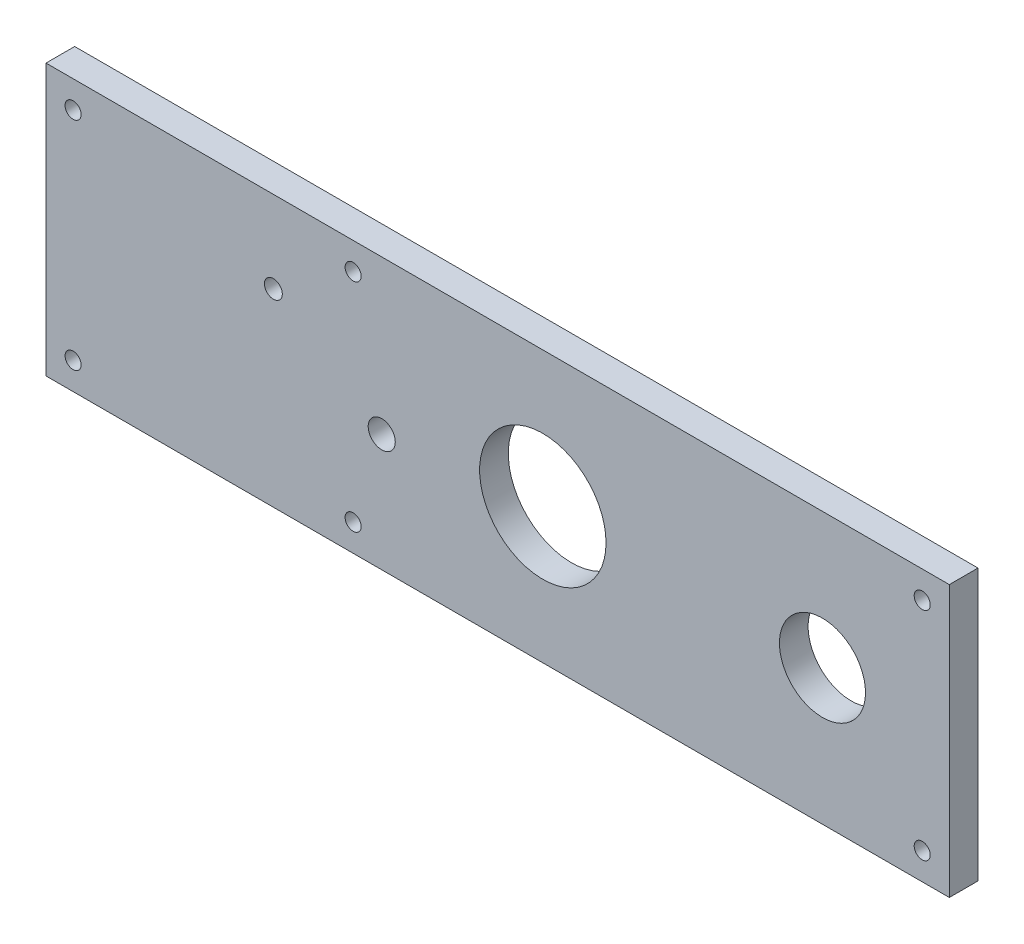
SolidWorks part; units mm, degrees
ref_plane "Front Plane" through (0, 0, 0) normal (0, 0, 1) x (1, 0, 0)
ref_plane "Top Plane" through (0, 0, 0) normal (0, 1, 0) x (1, 0, 0)
ref_plane "Right Plane" through (0, 0, 0) normal (1, 0, 0) x (0, 0, -1)
sketch "Sketch1" plane through (0, 0, 0) normal (0, 0, 1) x (1, 0, 0)
  line L0 (100, 15) -> (0, 15) construction
  line L1 (0, 0) -> (100, 0)
  line L2 (0, 0) -> (0, 30)
  line L3 (0, 30) -> (100, 30)
  line L4 (100, 0) -> (100, 30)
  circle A0 centre (55, 15) radius 6.9977
  circle A1 centre (37.1667, 13) radius 1.4986
  circle A2 centre (25.1698, 20.9334) radius 0.9906
  circle A3 centre (37.1667, 13) radius 11.4777 construction
  circle A4 centre (25.1698, 20.9334) radius 7.1501 construction
  circle A5 centre (55, 15) radius 12.827 construction
  circle A6 centre (16, 15) radius 14 construction
  circle A7 centre (37.1667, 13) radius 5.1181 construction
  point P7 (55, 15)
  point P8 (37.1667, 13)
  point P9 (25.1698, 20.9334)
  point P19 (16, 15)
  dimension "D6" = 13.9954
  dimension "D7" = 2.9972
  dimension "D8" = 1.9812
  dimension "D9" = 25.654
  dimension "D10" = 22.9553
  dimension "D11" = 14.3002
  dimension "D13" = 28
  dimension "D14" = 10.2362
  dimension "D1" = 17.9451
  dimension "D2" = 14.3828
  dimension "D3" = 30
  dimension "D4" = 100
  dimension "D5" = 55
  dimension "D12" = 10.922
  dimension "D15" = 16
  dimension "D16" = 13
extrude "Boss-Extrude2" add sketch "Sketch1" along normal blind 3.175
hole_wizard "#2-56 Tapped Hole1" positions "Sketch3" profile "Sketch2" tap size "#2-56" standard "ANSI Inch" end condition through all
sketch "Sketch3" plane through (0, 0, 3.175) normal (0, 0, 1) x (1, 0, 0)
  line L0 (97, 30) -> (97, 0) construction
  line L1 (100, 30) -> (0, 30) construction
  line L2 (0, 0) -> (100, 0) construction
  line L4 (100, 0) -> (100, 30) construction
  line L6 (3, 30) -> (3, 0) construction
  line L8 (0, 30) -> (0, 0) construction
  line L10 (34, 30) -> (34, 0) construction
  point P12 (97, 27)
  point P14 (97, 3)
  point P28 (3, 27)
  point P30 (3, 3)
  point P36 (34, 27)
  point P38 (34, 3)
  dimension "D1" = 3
  dimension "D2" = 3
  dimension "D3" = 3
  dimension "D4" = 3
  dimension "D5" = 3
  dimension "D6" = 3
  dimension "D7" = 34
sketch "Sketch2" plane through (97, 27, 3.175) normal (1, 0, 0) x (0, -1, 0)
  line L0 (0, 0) -> (0, 3.175)
  line L1 (0, 3.175) -> (0.889, 3.175)
  line L2 (0.889, 3.175) -> (0.889, 0)
  line L5 (0.889, 0) -> (0, 0)
  line L11 (0, -6.35) -> (0, 107.95) construction
  dimension "Thread Major Dia." = 1.778
  dimension "Thru Tap Drill Depth" = 3.175
sketch "Sketch4" plane through (0, 0, 3.175) normal (0, 0, 1) x (1, 0, 0)
  line L0 (0, 15) -> (100, 15) construction
  line L1 (0, 30) -> (0, 0) construction
  line L2 (100, 0) -> (100, 30) construction
  circle A0 centre (85.9562, 15) radius 4.7625
  circle A1 centre (55, 15) radius 6.9977 construction
  dimension "D1" = 9.525
  dimension "D2" = 30.9562
extrude "Cut-Extrude1" cut sketch "Sketch4" against normal through all
